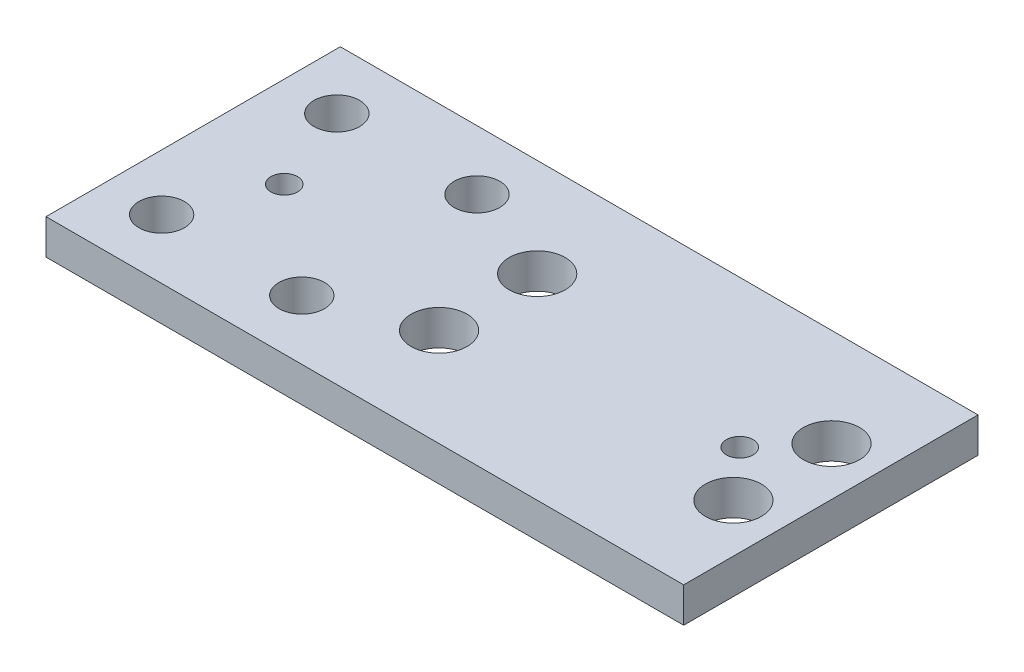
SolidWorks part; units mm, degrees
ref_plane "정면" through (0, 0, 0) normal (0, 0, 1) x (1, 0, 0)
ref_plane "윗면" through (0, 0, 0) normal (0, 1, 0) x (1, 0, 0)
ref_plane "우측면" through (0, 0, 0) normal (1, 0, 0) x (0, 0, -1)
sketch "스케치1" plane through (0, 0, 0) normal (0, 1, 0) x (1, 0, 0)
  line L1 (0, 0) -> (91, 0)
  line L2 (0, 0) -> (0, 42)
  line L3 (0, 42) -> (91, 42)
  line L4 (91, 0) -> (91, 42)
  dimension "D1" = 91
  dimension "D2" = 42
extrude "보스-돌출1" add sketch "스케치1" along normal blind 5
sketch "스케치2" plane through (0, 5, 0) normal (0, 1, 0) x (1, 0, 0)
  line L0 (0, 42) -> (0, 0) construction
  line L1 (8, 33.5) -> (28, 33.5) construction
  line L2 (8, 33.5) -> (8, 8.5) construction
  line L3 (8, 8.5) -> (28, 8.5) construction
  line L4 (28, 33.5) -> (28, 8.5) construction
  line L5 (91, 42) -> (0, 42) construction
  line L7 (84.0949, 28) -> (84.0949, 42) construction
  line L8 (42.0949, 28) -> (84.0949, 28) construction
  line L9 (42.0949, 28) -> (42.0949, 14) construction
  line L10 (42.0949, 14) -> (84.0949, 14) construction
  line L11 (84.0949, 28) -> (84.0949, 14) construction
  line L12 (84.0949, 14) -> (84.0949, 0) construction
  line L13 (0, 0) -> (91, 0) construction
  line L14 (91, 21) -> (78, 21) construction
  line L15 (91, 0) -> (91, 42) construction
  line L16 (78, 21) -> (13, 21) construction
  line L17 (13, 21) -> (0, 21) construction
  circle A0 centre (28, 33.5) radius 1.75
  circle A1 centre (28, 8.5) radius 1.75
  circle A2 centre (8, 8.5) radius 1.75
  circle A3 centre (8, 33.5) radius 1.75
  circle A4 centre (42.0949, 28) radius 2.25
  circle A5 centre (42.0949, 14) radius 2.25
  circle A6 centre (84.0949, 14) radius 2.25
  circle A7 centre (84.0949, 28) radius 2.25
  circle A8 centre (78, 21) radius 1.9
  circle A9 centre (13, 21) radius 1.9
  dimension "D5" = 3.5
  dimension "D8" = 4.5
  dimension "D10" = 3.8
  dimension "D1" = 8
  dimension "D2" = 8.5
  dimension "D3" = 25
  dimension "D4" = 20
  dimension "D6" = 14
  dimension "D7" = 42
  dimension "D9" = 65
extrude "컷-돌출1" cut sketch "스케치2" against normal blind 5
sketch "스케치3" plane through (0, 5, 0) normal (0, 1, 0) x (1, 0, 0)
  circle A0 centre (84.0949, 28) radius 4
  circle A1 centre (84.0949, 14) radius 4
  circle A2 centre (42.0949, 14) radius 4
  circle A3 centre (42.0949, 28) radius 4
  circle A4 centre (28, 33.5) radius 3.25
  circle A5 centre (28, 8.5) radius 3.25
  circle A6 centre (8, 8.5) radius 3.25
  circle A7 centre (8, 33.5) radius 3.25
  dimension "D1" = 8
  dimension "D2" = 6.5
extrude "컷-돌출2" cut sketch "스케치3" against normal blind 5
